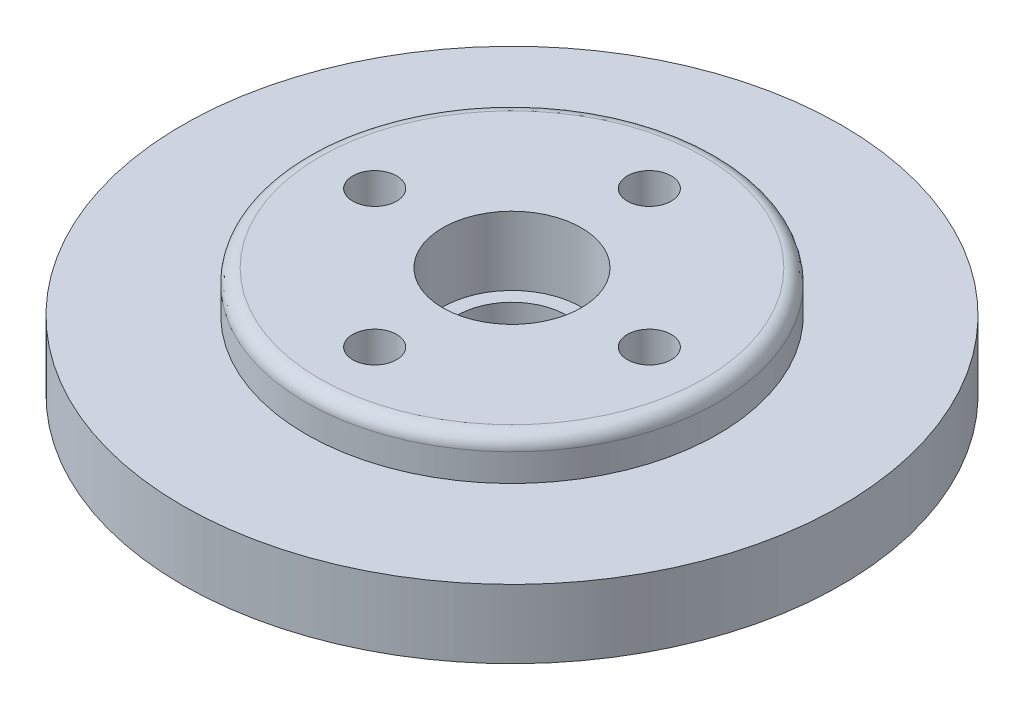
SolidWorks part; units mm, degrees
ref_plane "Front Plane" through (0, 0, 0) normal (0, 0, 1) x (1, 0, 0)
ref_plane "Top Plane" through (0, 0, 0) normal (0, 1, 0) x (1, 0, 0)
ref_plane "Right Plane" through (0, 0, 0) normal (1, 0, 0) x (0, 0, -1)
sketch "Sketch1" plane through (0, 0, 0) normal (0, 1, 0) x (1, 0, 0)
  circle A0 centre (0, 0) radius 24
  circle A1 centre (0, 0) radius 4
  dimension "D1" = 48
  dimension "D2" = 8
extrude "Boss-Extrude1" add sketch "Sketch1" along normal blind 5
sketch "Sketch2" plane through (0, 5, 0) normal (0, 1, 0) x (1, 0, 0)
  circle A0 centre (0, 0) radius 15
  dimension "D1" = 30
extrude "Boss-Extrude2" add sketch "Sketch2" along normal blind 3
sketch "Sketch4" plane through (0, 8, 0) normal (0, 1, 0) x (1, 0, 0)
  circle A0 centre (0, 0) radius 5.05
  dimension "D1" = 10.1
extrude "Cut-Extrude2" cut sketch "Sketch4" against normal blind 5
fillet "Fillet1" radius 1 1 edges at (0, 8, 15)
sketch "Sketch5" plane through (0, 8, 0) normal (0, 1, 0) x (1, 0, 0)
  circle A0 centre (0, 0) radius 10 construction
  circle A1 centre (0, 10) radius 1.6
  circle A2 centre (-10, 0) radius 1.6
  circle A3 centre (0, -10) radius 1.6
  circle A4 centre (10, 0) radius 1.6
  dimension "D1" = 20
  dimension "D2" = 3.2
extrude "Cut-Extrude3" cut sketch "Sketch5" against normal through all contours A3 | A4 | A1 | A2
sketch "Sketch10" plane through (0, 0, 0) normal (0, -1, 0) x (1, 0, 0)
  line L0 (10, -3.1) -> (12.6847, -1.55)
  line L1 (3.1, 10) -> (1.55, 12.6847)
  line L2 (1.55, 12.6847) -> (-1.55, 12.6847)
  line L3 (-1.55, 12.6847) -> (-3.1, 10)
  line L4 (-3.1, 10) -> (-1.55, 7.3153)
  line L5 (-1.55, 7.3153) -> (1.55, 7.3153)
  line L6 (1.55, 7.3153) -> (3.1, 10)
  line L7 (12.6847, -1.55) -> (12.6847, 1.55)
  line L8 (12.6847, 1.55) -> (10, 3.1)
  line L9 (10, 3.1) -> (7.3153, 1.55)
  line L10 (7.3153, 1.55) -> (7.3153, -1.55)
  line L11 (7.3153, -1.55) -> (10, -3.1)
  line L12 (-3.1, -10) -> (-1.55, -12.6847)
  line L13 (-1.55, -12.6847) -> (1.55, -12.6847)
  line L14 (1.55, -12.6847) -> (3.1, -10)
  line L15 (3.1, -10) -> (1.55, -7.3153)
  line L16 (1.55, -7.3153) -> (-1.55, -7.3153)
  line L17 (-1.55, -7.3153) -> (-3.1, -10)
  line L18 (-10, 3.1) -> (-12.6847, 1.55)
  line L19 (-12.6847, 1.55) -> (-12.6847, -1.55)
  line L20 (-12.6847, -1.55) -> (-10, -3.1)
  line L21 (-10, -3.1) -> (-7.3153, -1.55)
  line L22 (-7.3153, -1.55) -> (-7.3153, 1.55)
  line L23 (-7.3153, 1.55) -> (-10, 3.1)
  circle A0 centre (0, 10) radius 2.6847 construction
  dimension "D1" = 3.1
  dimension "D2" = 4
extrude "Cut-Extrude15" cut sketch "Sketch10" against normal blind 3
